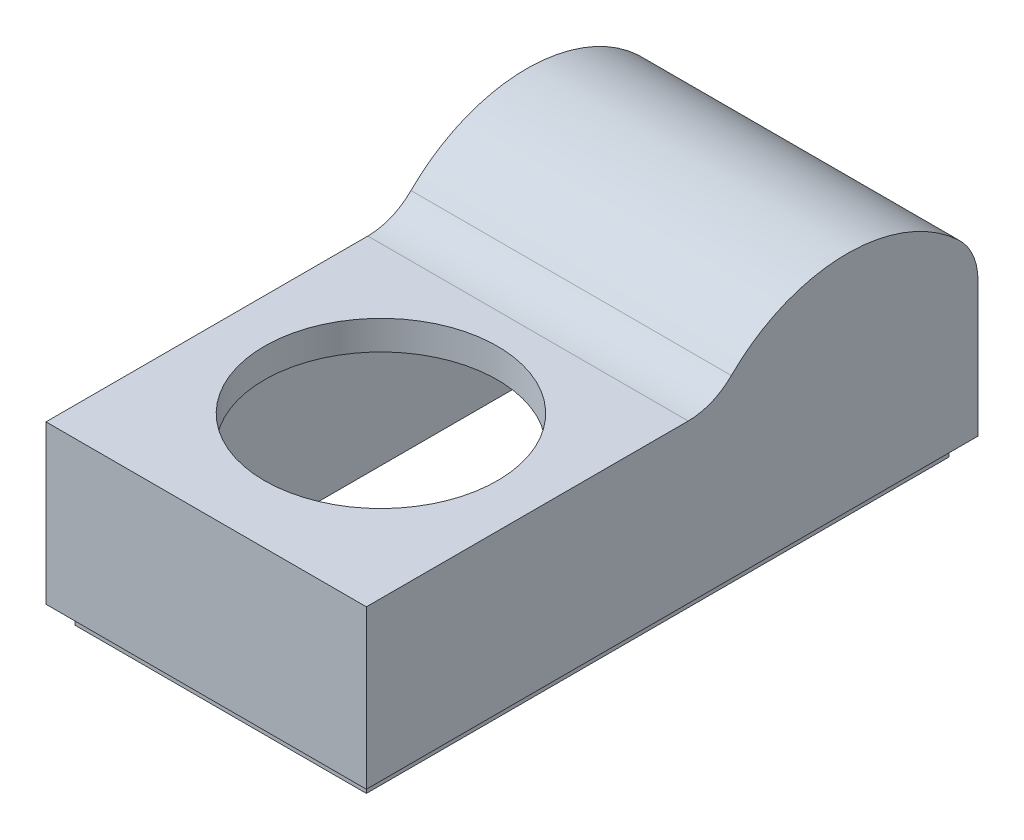
SolidWorks part; units mm, degrees
ref_plane "Front Plane" through (0, 0, 0) normal (0, 0, 1) x (1, 0, 0)
ref_plane "Top Plane" through (0, 0, 0) normal (0, 1, 0) x (1, 0, 0)
ref_plane "Right Plane" through (0, 0, 0) normal (1, 0, 0) x (0, 0, -1)
sketch "Sketch1" plane through (0, 0, 0) normal (0, 1, 0) x (1, 0, 0)
  line L1 (-13.97, 26.67) -> (13.97, 26.67)
  line L2 (-13.97, 26.67) -> (-13.97, -26.67)
  line L3 (-13.97, -26.67) -> (13.97, -26.67)
  line L4 (13.97, 26.67) -> (13.97, -26.67)
  point P4 (0, 26.67)
  point P6 (-13.97, 0)
  dimension "D1" = 53.34
  dimension "D2" = 27.94
extrude "Boss-Extrude1" add sketch "Sketch1" along normal mid plane 19.4945
sketch "Sketch2" plane through (13.97, 0, 0) normal (1, 0, 0) x (0, 0, -1)
  line L0 (-26.67, 4.0323) -> (3.81, 4.0323)
  line L1 (-26.67, 9.7472) -> (-26.67, -9.7472) construction
  line L2 (26.67, 9.7472) -> (26.67, -9.7472) construction
  line L8 (26.67, 4.0323) -> (26.67, 9.7472)
  line L9 (26.67, 9.7472) -> (-26.67, 9.7472)
  line L10 (-26.67, 9.7472) -> (-26.67, 4.0323)
  arc A0 (3.81, 4.0323) -> (26.67, 4.0323) centre (15.24, -4.5403) cw
  point P9 (15.24, 9.7473)
  line M3 (26.67, -9.7472) -> (26.67, 9.7472)
  line M4 (26.67, 9.7472) -> (-26.67, 9.7472)
  line M5 (-26.67, 9.7472) -> (-26.67, -9.7472)
  dimension "D1" = 5.715
  dimension "D3" = 22.86
extrude "Cut-Extrude1" cut sketch "Sketch2" against normal up to surface (27.94 mm away) contours L0 A0 L9 M5 | A0 M4 M3 up to face at (-13.97, 0, 0)
fillet "Fillet1" radius 5.334 1 edges at (0, 4.0323, -3.81)
fillet "Fillet2" radius 5.334 1 edges at (0, 4.0323, -26.67)
shell "Shell1" thickness 2.54
sketch "Sketch3" plane through (0, 4.0323, 0) normal (0, 1, 0) x (1, 0, 0)
  line L0 (-13.97, -11.43) -> (13.97, -11.43) construction
  line L1 (-13.97, 1.3976) -> (-13.97, -26.67) construction
  line L2 (13.97, -26.67) -> (13.97, 1.3976) construction
  line L4 (0, -1.27) -> (0, -21.59) construction
  line L5 (-13.97, -26.67) -> (13.97, -26.67) construction
  circle A0 centre (0, -11.43) radius 10.16
  point P9 (0, -11.43)
  dimension "D2" = 20.32
  dimension "D1" = 5.08
extrude "Cut-Extrude2" cut sketch "Sketch3" against normal blind 24.13
sketch "Sketch5" plane through (0, 0, -26.67) normal (0, 0, -1) x (-1, 0, 0)
  line L0 (-13.97, -9.7472) -> (13.97, -9.7472) construction
  line L1 (-5.3975, -9.7472) -> (5.3975, -9.7472)
  line L2 (-5.3975, -9.7472) -> (-5.3975, -8.1597)
  line L3 (-5.3975, -8.1597) -> (5.3975, -8.1597)
  line L4 (5.3975, -9.7472) -> (5.3975, -8.1597)
  point P6 (0, -8.1597)
  dimension "D1" = 1.5875
  dimension "D2" = 10.795
extrude "Cut-Extrude3" cut sketch "Sketch5" against normal up to surface (2.54 mm away) up to face at (0, -3.8649, -24.13)
sketch "Sketch4" plane through (0, -9.7472, 0) normal (0, -1, 0) x (1, 0, 0)
  line L0 (-5.3975, -24.13) -> (-11.43, -24.13) construction
  line L1 (11.43, -24.13) -> (5.3975, -24.13) construction
  line L2 (11.43, 24.13) -> (11.43, -24.13) construction
  line L3 (-11.43, 24.13) -> (11.43, 24.13) construction
  line L4 (-11.43, -24.13) -> (-11.43, 24.13) construction
  line L5 (-5.3975, -24.13) -> (-11.43, -24.13)
  line L6 (11.43, -24.13) -> (5.3975, -24.13)
  line L7 (11.43, 24.13) -> (11.43, -24.13)
  line L8 (-11.43, 24.13) -> (11.43, 24.13)
  line L9 (-11.43, -24.13) -> (-11.43, 24.13)
  line L10 (-5.3975, -25.4) -> (-5.3975, -24.13)
  line L11 (5.3975, -25.4) -> (5.3975, -24.13)
  line L56 (-12.7, 25.4) -> (-12.7, -25.4)
  line L57 (-12.7, -25.4) -> (-5.3975, -25.4)
  line L58 (-5.3975, -25.4) -> (5.3975, -25.4)
  line L59 (5.3975, -25.4) -> (12.7, -25.4)
  line L60 (12.7, -25.4) -> (12.7, 25.4)
  line L61 (12.7, 25.4) -> (-12.7, 25.4)
  line L62 (-12.7, 25.4) -> (-12.7, -25.4)
  line L63 (-12.7, -25.4) -> (-5.3975, -25.4)
  line L65 (5.3975, -25.4) -> (12.7, -25.4)
  line L66 (12.7, -25.4) -> (12.7, 25.4)
  line L67 (12.7, 25.4) -> (-12.7, 25.4)
  dimension "D1" = 1.27
extrude "Boss-Extrude2" add sketch "Sketch4" along normal blind 1.5875
